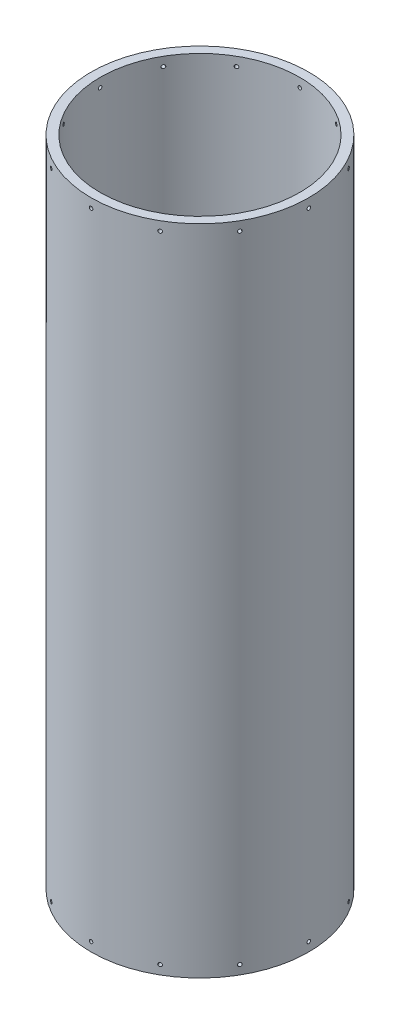
SolidWorks part; units mm, degrees
ref_plane "Front Plane" through (0, 0, 0) normal (0, 0, 1) x (1, 0, 0)
ref_plane "Top Plane" through (0, 0, 0) normal (0, 1, 0) x (1, 0, 0)
ref_plane "Right Plane" through (0, 0, 0) normal (1, 0, 0) x (0, 0, -1)
sketch "Sketch1" plane through (0, 0, 0) normal (0, 1, 0) x (1, 0, 0)
  circle A0 centre (0, 0) radius 152.4
  circle A1 centre (0, 0) radius 139.7
  dimension "D2" = 304.8
  dimension "D1" = 279.4
extrude "Boss-Extrude1" add sketch "Sketch1" along normal blind 914.4
ref_plane "Plane1" through (-152.4, 0, 0) normal (-1, 0, 0) x (0, 0, 1)
hole_wizard "#10 (0.1935) Diameter Hole1" positions "Sketch2" profile "Sketch3" hole size "#10" standard "ANSI Inch"
sketch "Sketch2" plane through (-152.4, 0, 0) normal (-1, 0, 0) x (0, 0, 1)
  line L0 (0, -167.64) -> (0, 167.64) construction
  line L1 (152.4, 914.4) -> (-152.4, 914.4) construction
  point P0 (0, 901.7)
  dimension "D1" = 12.7
sketch "Sketch3" plane through (-152.4, 901.7, 0) normal (0, 1, 0) x (0, 0, 1)
  line L0 (0, 0) -> (0, 343.2351)
  line L1 (0, 343.2351) -> (2.4574, 343.2351)
  line L2 (2.4574, 343.2351) -> (2.4574, 0)
  line L5 (2.4574, 0) -> (0, 0)
  line L11 (0, -6.35) -> (0, 107.95) construction
  dimension "Thru Hole Dia." = 4.9149
  dimension "Thru Hole Depth" = 343.2351
pattern_circular "CirPattern1" count 12 over 360 about axis through (0, 914.4, 0) along (0, 1, 0) of "#10 (0.1935) Diameter Hole1"
ref_plane "Plane2" through (0, 457.2, 0) normal (0, 1, 0) x (1, 0, 0)
mirror "Mirror1" about plane through (0, 457.2, 0) normal (0, 1, 0) of "CirPattern1", "#10 (0.1935) Diameter Hole1"
